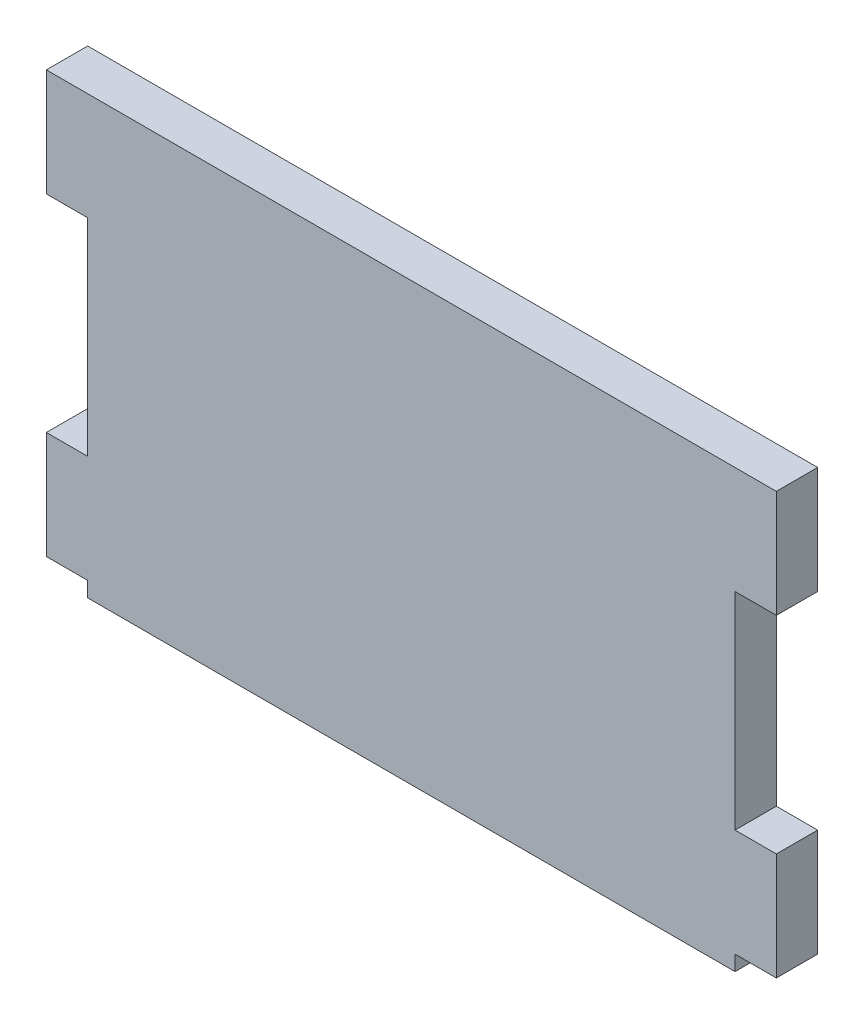
SolidWorks part; units mm, degrees
ref_plane "Front Plane" through (0, 0, 0) normal (0, 0, 1) x (1, 0, 0)
ref_plane "Top Plane" through (0, 0, 0) normal (0, 1, 0) x (1, 0, 0)
ref_plane "Right Plane" through (0, 0, 0) normal (1, 0, 0) x (0, 0, -1)
sketch "Sketch1" plane through (0, 0, 0) normal (0, 0, 1) x (1, 0, 0)
  line L1 (-40.9935, 16.542) -> (12.0065, 16.542)
  line L2 (-40.9935, 16.542) -> (-40.9935, -15.158)
  line L3 (-40.9935, -15.158) -> (12.0065, -15.158)
  line L4 (12.0065, 16.542) -> (12.0065, -15.158)
  dimension "D1" = 31.7
  dimension "D2" = 53
extrude "Boss-Extrude1" add sketch "Sketch1" along normal blind 3
sketch "Sketch2" plane through (0, 0, 3) normal (0, 0, 1) x (1, 0, 0)
  line L0 (-40.9935, 16.542) -> (-40.9935, -15.158) construction
  line L1 (-40.9935, 8.742) -> (-37.9935, 8.742)
  line L2 (-40.9935, 8.742) -> (-40.9935, -6.258)
  line L3 (-40.9935, -6.258) -> (-37.9935, -6.258)
  line L4 (-37.9935, 8.742) -> (-37.9935, -6.258)
  line L5 (12.0065, 16.542) -> (-40.9935, 16.542) construction
  line L6 (12.0065, -15.158) -> (12.0065, 16.542) construction
  line L7 (12.0065, 8.742) -> (9.0065, 8.742)
  line L8 (12.0065, 8.742) -> (12.0065, -6.258)
  line L9 (12.0065, -6.258) -> (9.0065, -6.258)
  line L10 (9.0065, 8.742) -> (9.0065, -6.258)
  point P8 (-39.4935, 8.742)
  dimension "D1" = 3
  dimension "D2" = 7.8
  dimension "D3" = 15
  dimension "D4" = 3
  dimension "D5" = 7.8
  dimension "D6" = 15
extrude "Cut-Extrude1" cut sketch "Sketch2" against normal through all
pattern_linear "LPattern1" count 3 spacing 22.8 along (0, -1, 0) of "Cut-Extrude1"
